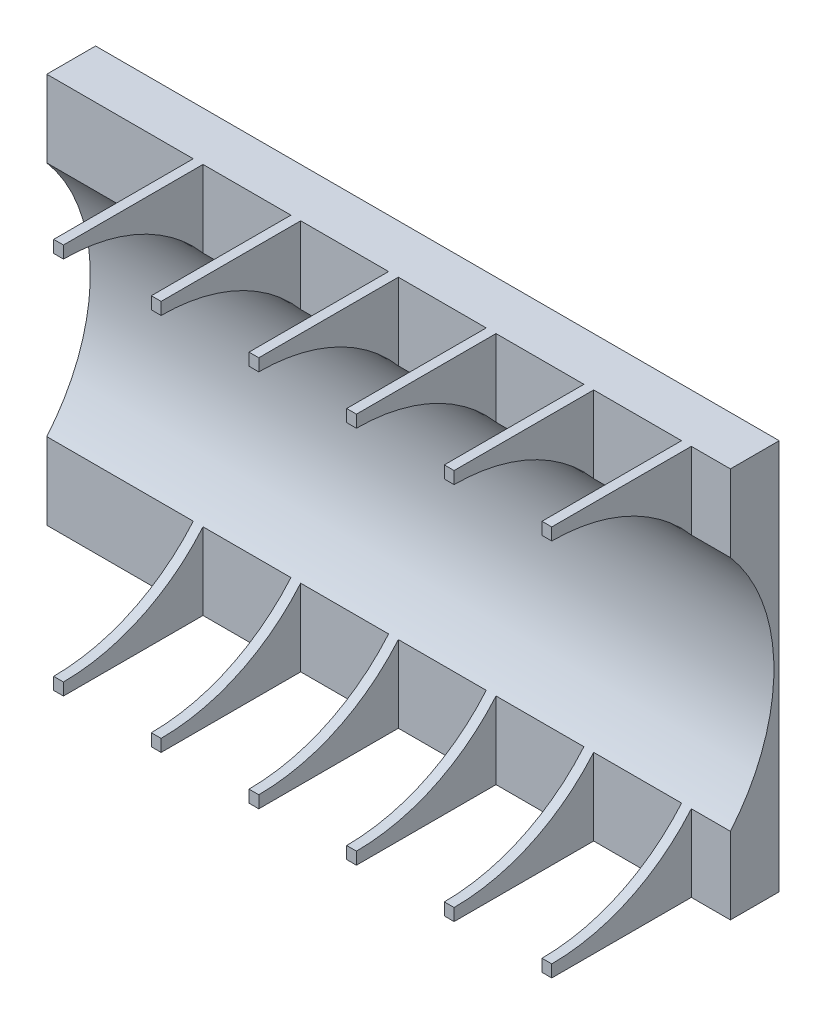
SolidWorks part; units mm, degrees
ref_plane "Front Plane" through (0, 0, 0) normal (0, 0, 1) x (1, 0, 0)
ref_plane "Top Plane" through (0, 0, 0) normal (0, 1, 0) x (1, 0, 0)
ref_plane "Right Plane" through (0, 0, 0) normal (1, 0, 0) x (0, 0, -1)
sketch "Sketch1" plane through (0, 0, 0) normal (0, 0, 1) x (1, 0, 0)
  line L4 (0, 0) -> (700, 0)
  line L5 (700, 0) -> (700, 400)
  line L6 (700, 400) -> (0, 400)
  line L7 (0, 400) -> (0, 0)
  dimension "D1" = 700
  dimension "D2" = 400
extrude "Boss-Extrude2" add sketch "Sketch1" along normal blind 50
ref_plane "Plane4" through (650, 0, 0) normal (1, 0, 0) x (0, 0, -1)
sketch "Sketch2" plane through (650, 0, 0) normal (1, 0, 0) x (0, 0, -1)
  line L0 (-50, 0) -> (-192.9278, 0)
  line L1 (-192.9278, 0) -> (-192.9278, 12.5)
  line L2 (-192.9278, 387.5) -> (-192.9278, 400)
  line L3 (-192.9278, 400) -> (-50, 400)
  line L4 (-50, 0) -> (0, 0)
  line L5 (0, 0) -> (0, 400)
  line L6 (0, 400) -> (-50, 400)
  arc A0 (-192.9278, 12.5) -> (-192.9278, 387.5) centre (-192.9278, 200) ccw
  dimension "D1" = 12.5
extrude "Boss-Extrude3" add sketch "Sketch2" along normal blind 10
sketch "Sketch3" plane through (650, 0, 0) normal (1, 0, 0) x (0, 0, -1)
  line L0 (-50, 78.6415) -> (-50, 321.3585)
  arc A0 (-50, 78.6415) -> (-50, 321.3585) centre (-192.9278, 200) ccw
extrude "Cut-Extrude1" cut sketch "Sketch3" against normal through all both and the other way through all
pattern_linear "LPattern1" count 6 spacing 100 along (-1, 0, 0) of "Boss-Extrude3"
